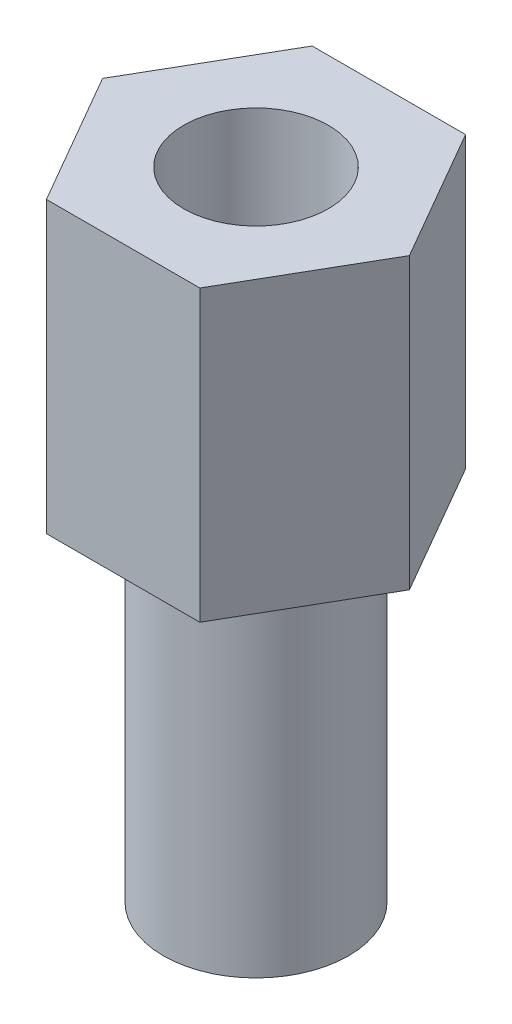
SolidWorks part; units mm, degrees
ref_plane "前视基准面" through (0, 0, 0) normal (0, 0, 1) x (1, 0, 0)
ref_plane "上视基准面" through (0, 0, 0) normal (0, 1, 0) x (1, 0, 0)
ref_plane "右视基准面" through (0, 0, 0) normal (1, 0, 0) x (0, 0, -1)
sketch "草图4" plane through (0, 0, 0) normal (0, 1, 0) x (1, 0, 0)
  line L0 (-12.7945, 0) -> (16.3015, 0) construction
  line L2 (1.325, -2.295) -> (2.65, 0)
  line L3 (2.65, 0) -> (1.325, 2.295)
  line L4 (1.325, 2.295) -> (-1.325, 2.295)
  line L5 (-1.325, 2.295) -> (-2.65, 0)
  line L6 (-2.65, 0) -> (-1.325, -2.295)
  line L7 (-1.325, -2.295) -> (1.325, -2.295)
  circle A0 centre (0, 0) radius 2.295 construction
  dimension "D1" = 5.3
extrude "凸台-拉伸1" add sketch "草图4" along normal blind 5
sketch "草图6" plane through (0, 0, 0) normal (0, -1, 0) x (-1, 0, 0)
  circle A0 centre (0, 0) radius 1.6
  dimension "D1" = 3.2
extrude "凸台-拉伸2" add sketch "草图6" along normal blind 6
cosmetic thread "装饰螺纹线1" parameters "D2"=2.5
sketch "草图7" plane through (0, 5, 0) normal (0, 1, 0) x (1, 0, 0)
  circle A0 centre (0, 0) radius 1.25
  dimension "D1" = 2.5
extrude "切除-拉伸1" cut sketch "草图7" against normal blind 5
cosmetic thread "装饰螺纹线2" parameters "D2"=3
